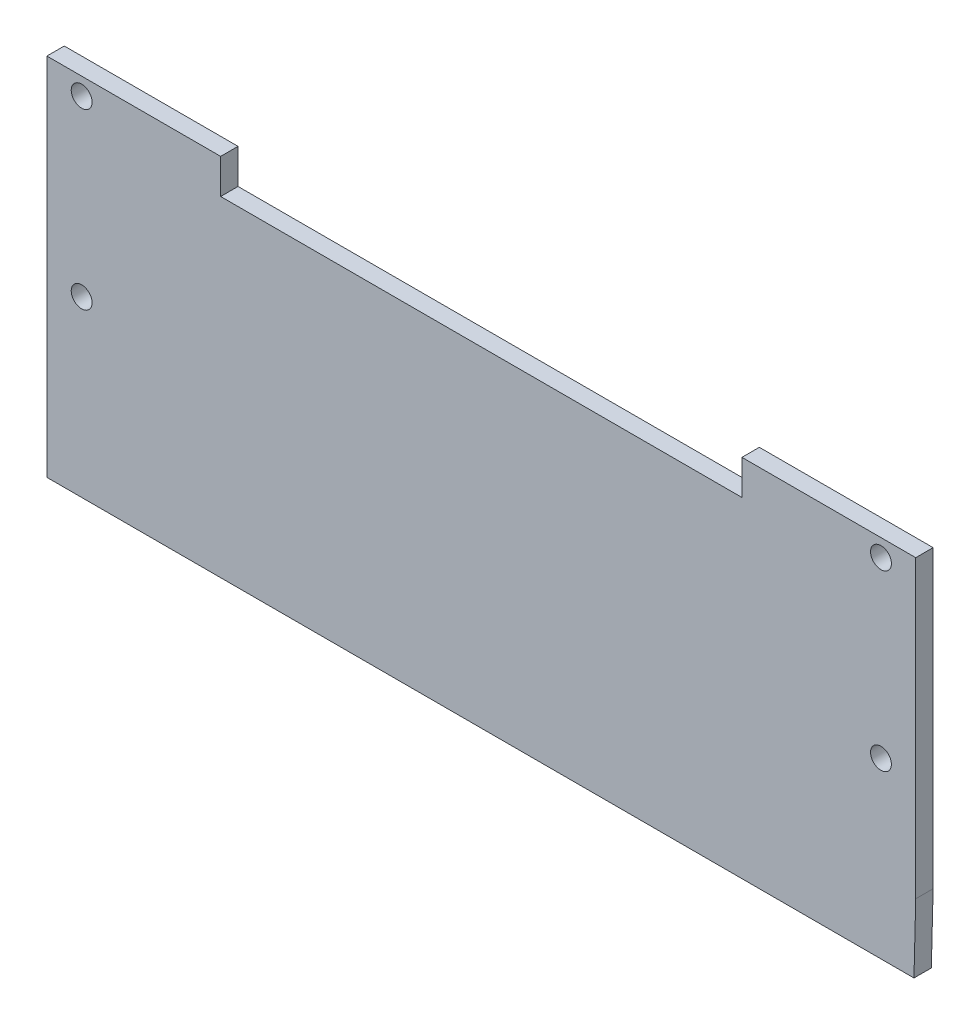
SolidWorks part; units mm, degrees
ref_plane "Plan de face" through (0, 0, 0) normal (0, 0, 1) x (1, 0, 0)
ref_plane "Plan de dessus" through (0, 0, 0) normal (0, 1, 0) x (1, 0, 0)
ref_plane "Plan de droite" through (0, 0, 0) normal (1, 0, 0) x (0, 0, -1)
sketch "Esquisse1" plane through (0, 0, 0) normal (0, 0, 1) x (1, 0, 0)
  line L0 (125, 0) -> (125, -85) construction
  line L1 (0, 0) -> (250, 0)
  line L2 (0, 0) -> (0, -85)
  line L3 (0, -85) -> (250, -85)
  line L4 (250, 0) -> (250, -85)
  circle A0 centre (10, -5) radius 3
  circle A1 centre (10, -55) radius 3
  circle A2 centre (240, -55) radius 3
  circle A3 centre (240, -5) radius 3
  dimension "D3" = 6
  dimension "D4" = 6
  dimension "D1" = 250
  dimension "D2" = 85
  dimension "D5" = 5
  dimension "D6" = 10
  dimension "D7" = 30
  dimension "D8" = 10
extrude "Boss.-Extru.1" add sketch "Esquisse1" along normal blind 5
sketch "Esquisse2" plane through (0, 0, 5) normal (0, 0, 1) x (1, 0, 0)
  line L0 (0, -85) -> (0, -105)
  line L1 (0, -105) -> (249.4914, -105)
  line L2 (249.4914, -105) -> (250, -85)
  line L3 (0, -85) -> (250, -85) construction
  line L4 (0, -85) -> (250, -85)
  dimension "D1" = 20
extrude "Boss.-Extru.2" add sketch "Esquisse2" against normal blind 5
sketch "Esquisse3" plane through (0, 0, 0) normal (0, 0, -1) x (-1, 0, 0)
  line L0 (-50, 0) -> (-200, 0)
  line L2 (-200, 0) -> (-200, -10)
  line L3 (-200, -10) -> (-50, -10)
  line L4 (-50, -10) -> (-50, 0)
  line L6 (0, 0) -> (0, -105) construction
  line L7 (-250, 0) -> (0, 0) construction
  point P4 (0, 0)
  dimension "D1" = 10
  dimension "D2" = 150
  dimension "D3" = 50
extrude "Enlèv. mat.-Extru.1" cut sketch "Esquisse3" against normal blind 10
